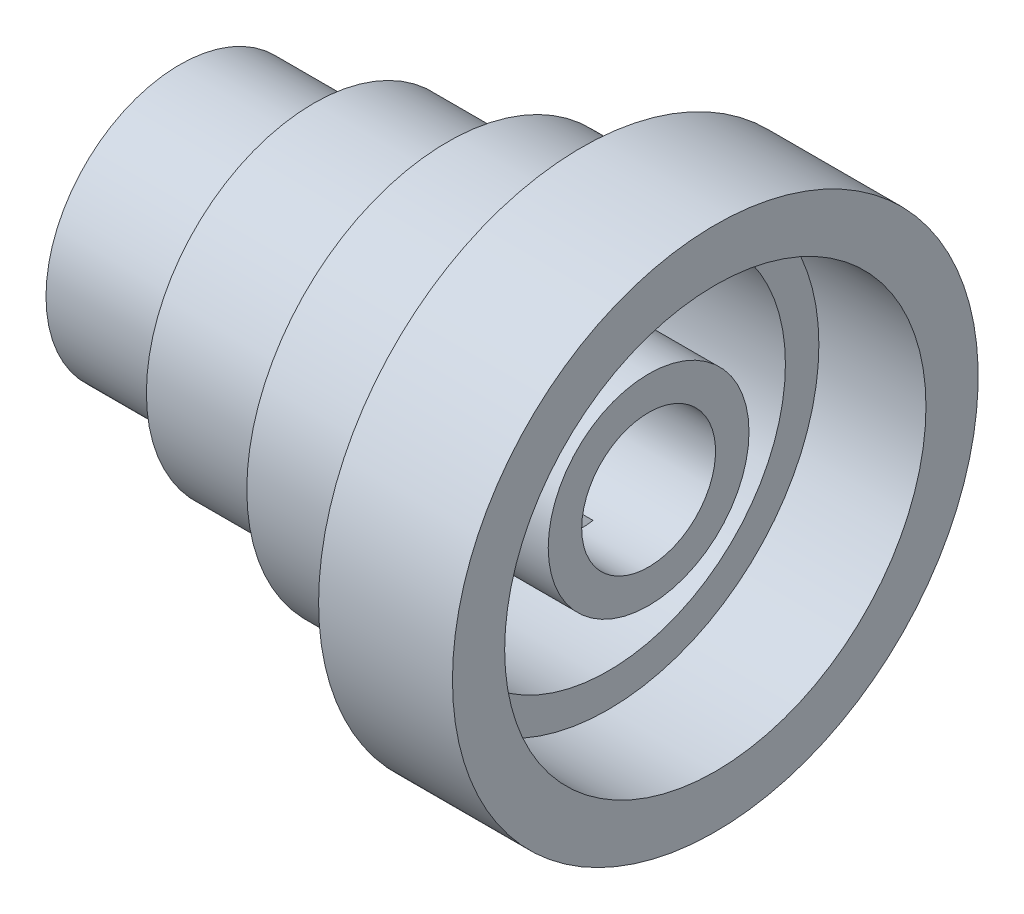
SolidWorks part; units mm, degrees
ref_plane "Front Plane" through (0, 0, 0) normal (0, 0, 1) x (1, 0, 0)
ref_plane "Top Plane" through (0, 0, 0) normal (0, 1, 0) x (1, 0, 0)
ref_plane "Right Plane" through (0, 0, 0) normal (1, 0, 0) x (0, 0, -1)
sketch "Sketch1" plane through (0, 0, 0) normal (0, 1, 0) x (1, 0, 0)
  line L0 (-87.474, 0) -> (138.9619, 0) construction
  line L1 (-87.474, 20) -> (52.5952, 20)
  line L2 (52.5952, 20) -> (52.5952, 30)
  line L3 (52.5952, 30) -> (-39.474, 30)
  line L4 (-39.474, 30) -> (-39.474, 40)
  line L5 (-39.474, 40) -> (0.526, 40)
  line L6 (0.526, 40) -> (0.526, 52.9481)
  line L7 (0.526, 52.9481) -> (40.526, 52.9481)
  line L8 (40.526, 52.9481) -> (40.526, 62.9481)
  line L9 (40.526, 62.9481) -> (72.526, 62.9481)
  line L10 (72.526, 62.9481) -> (72.526, 78.5467)
  line L11 (72.526, 78.5467) -> (32.526, 78.5467)
  line L12 (32.526, 78.5467) -> (32.526, 60)
  line L13 (32.526, 60) -> (-7.474, 60)
  line L14 (-7.474, 60) -> (-7.474, 50)
  line L15 (-7.474, 50) -> (-47.474, 50)
  line L16 (-47.474, 50) -> (-47.474, 40)
  line L17 (-47.474, 40) -> (-87.474, 40)
  line L18 (-87.474, 40) -> (-87.474, 20)
  dimension "D1" = 40
  dimension "D2" = 40
  dimension "D3" = 40
  dimension "D4" = 40
  dimension "D5" = 40
  dimension "D6" = 30
  dimension "D7" = 20
  dimension "D8" = 10
  dimension "D9" = 10
  dimension "D10" = 10
  dimension "D11" = 8
  dimension "D12" = 8
  dimension "D13" = 8
  dimension "D14" = 10
revolve "Revolve1" add sketch "Sketch1" angle 360 about L0
sketch "Sketch2" plane through (-87.474, 0, 0) normal (-1, 0, 0) x (0, 0, 1)
  line L0 (-3.4702, -25.7868) -> (-3.4702, -19.6966)
  line L1 (-3.4702, -25.7868) -> (6.8633, -25.7868)
  line L2 (6.8633, -25.7868) -> (6.8633, -18.7855)
  line L3 (-3.4702, -19.6966) -> (6.8633, -18.7855)
  circle A0 centre (0, 0) radius 20 construction
  point P4 (6.8633, -25.7868)
extrude "Cut-Extrude2" cut sketch "Sketch2" against normal blind 120
